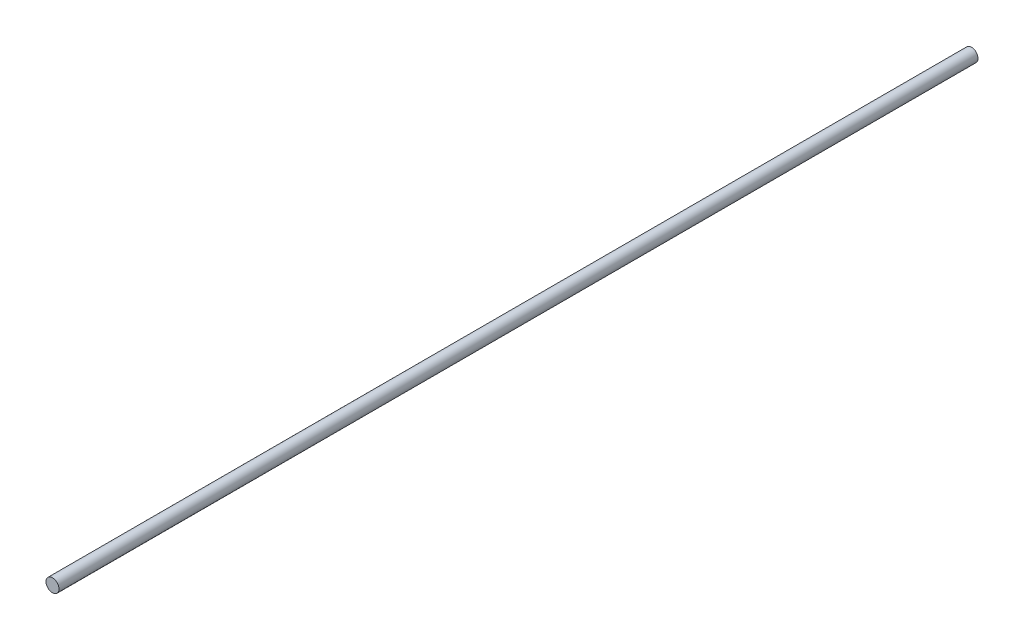
SolidWorks part; units mm, degrees
ref_plane "Ebene vorne" through (0, 0, 0) normal (0, 0, 1) x (1, 0, 0)
ref_plane "Ebene oben" through (0, 0, 0) normal (0, 1, 0) x (1, 0, 0)
ref_plane "Ebene rechts" through (0, 0, 0) normal (1, 0, 0) x (0, 0, -1)
sketch "Skizze1" plane through (0, 0, 0) normal (0, 0, 1) x (1, 0, 0)
  circle A0 centre (0, 0) radius 1.5
  dimension "D1" = 3
extrude "Aufsatz-Linear austragen1" add sketch "Skizze1" along normal blind 212
